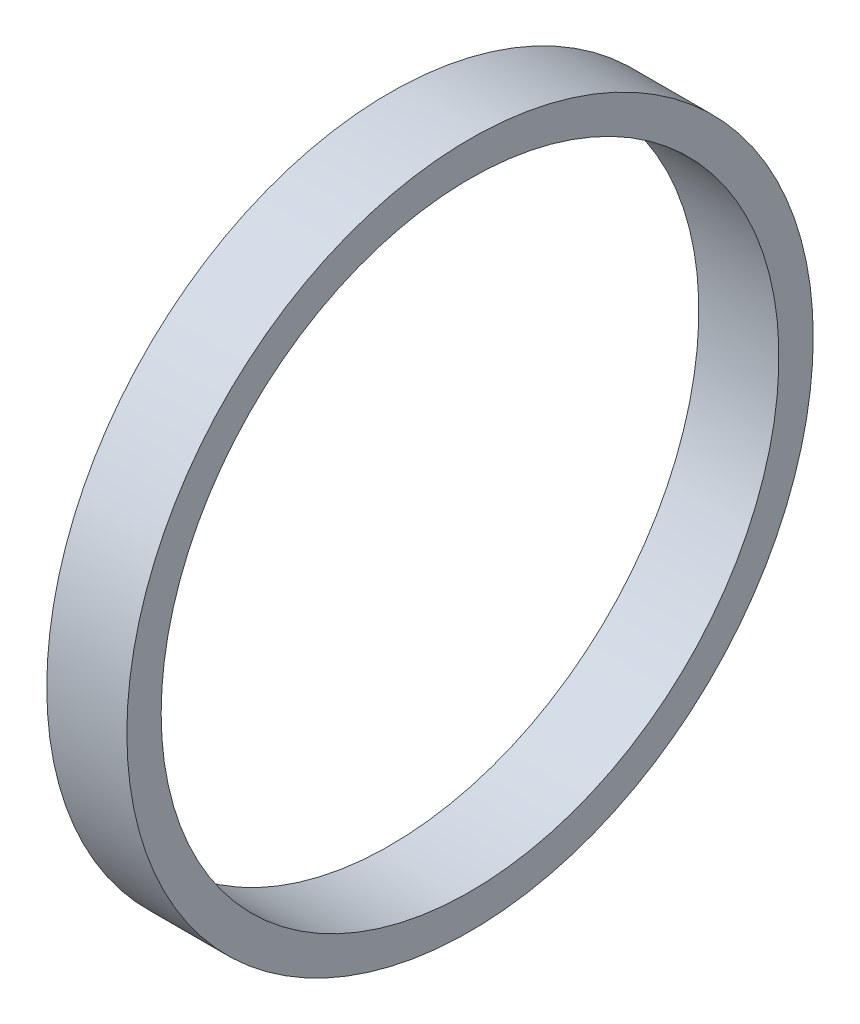
SolidWorks part; units mm, degrees
ref_plane "Plan de face" through (0, 0, 0) normal (0, 0, 1) x (1, 0, 0)
ref_plane "Plan de dessus" through (0, 0, 0) normal (0, 1, 0) x (1, 0, 0)
ref_plane "Plan de droite" through (0, 0, 0) normal (1, 0, 0) x (0, 0, -1)
sketch "Esquisse1" plane through (0, 0, 0) normal (0, 0, 1) x (1, 0, 0)
  line L0 (0, 0) -> (9.0042, 0) construction
  line L1 (0, 27) -> (7, 27)
  line L2 (7, 27) -> (7, 30)
  line L3 (7, 30) -> (0, 30)
  line L4 (0, 30) -> (0, 27)
  point P7 (0, 0)
  dimension "D1" = 7
  dimension "D2" = 3
  dimension "D3" = 30
revolve "Révolution1" add sketch "Esquisse1" angle 360 about L0
